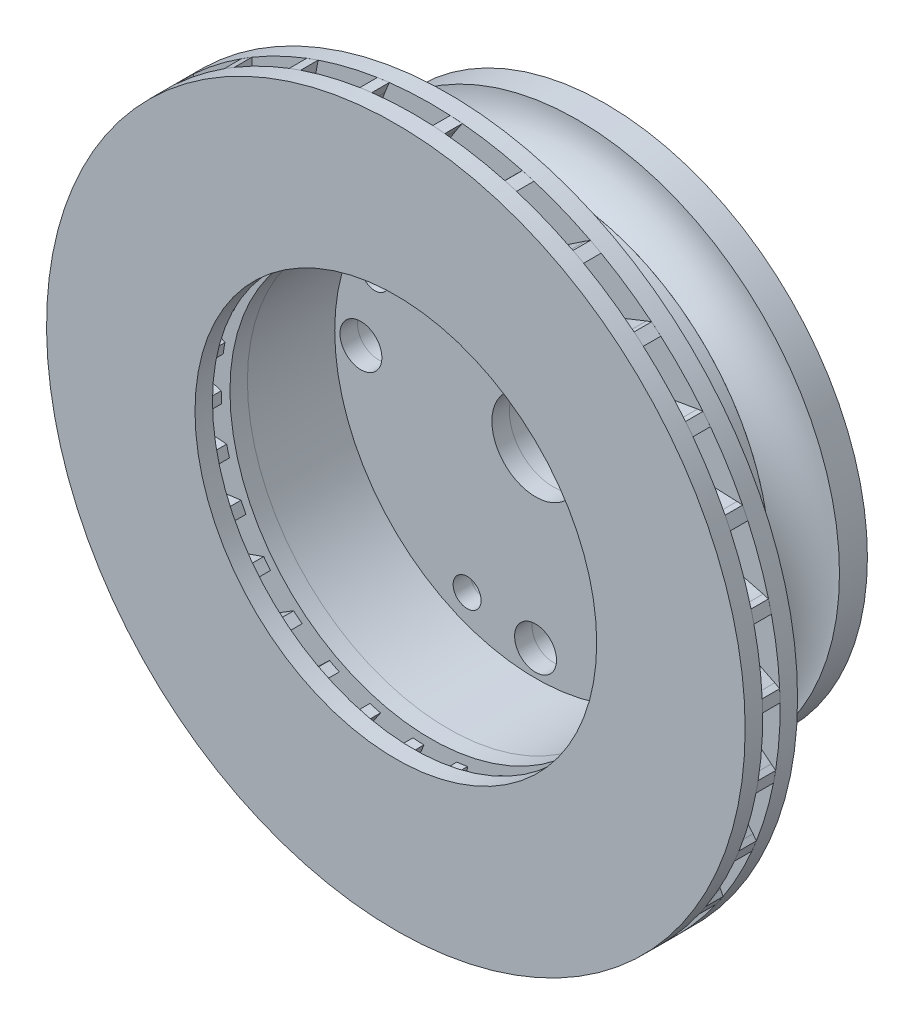
SolidWorks part; units mm, degrees
ref_plane "Front Plane" through (0, 0, 0) normal (0, 0, 1) x (1, 0, 0)
ref_plane "Top Plane" through (0, 0, 0) normal (0, 1, 0) x (1, 0, 0)
ref_plane "Right Plane" through (0, 0, 0) normal (1, 0, 0) x (0, 0, -1)
sketch "Sketch3" plane through (0, 0, 0) normal (1, 0, 0) x (0, 0, -1)
  line L0 (0, 0) -> (0, 75)
  line L1 (0, 75) -> (-8, 75)
  line L2 (-15, 62) -> (-15, 0)
  line L3 (-15, 0) -> (0, 0)
  line L4 (-15, 0) -> (-15.9175, 0)
  arc A0 (-8, 75) -> (-15, 62) centre (-23.5714, 75) cw
  point P10 (-5, 70)
  dimension "D1" = 8
  dimension "D2" = 75
  dimension "D3" = 13
  dimension "D4" = 15
  dimension "D5" = 0
revolve "Revolve1" add sketch "Sketch3" angle 360 about L4
sketch "Sketch4" plane through (0, 0, 15) normal (0, 0, 1) x (1, 0, 0)
  circle A2 centre (0, 0) radius 62
  circle A3 centre (0, 0) radius 62
  dimension "D1" = 0
extrude "Boss-Extrude2" add sketch "Sketch4" along normal blind 30 separate body
sketch "Sketch5" plane through (0, 0, 45) normal (0, 0, 1) x (1, 0, 0)
  circle A0 centre (0, 0) radius 100
  dimension "D1" = 200
extrude "Boss-Extrude3" add sketch "Sketch5" along normal blind 5 separate body
sketch "Sketch6" plane through (0, 0, 50) normal (0, 0, 1) x (1, 0, 0)
  line L0 (0, 0) -> (0, 8.2778)
  line L1 (44.3489, 88.0949) -> (45.7099, 88.9416)
  line L2 (45.9335, 85.5476) -> (47.2945, 86.3942)
  line L3 (47.2945, 86.3942) -> (48.7607, 87.3063)
  line L4 (48.7607, 87.3063) -> (45.7099, 88.9416)
  circle A1 centre (0, 0) radius 100 construction
  arc A2 (14.3838, 58.2504) -> (44.3489, 88.0949) centre (94, 8.2778) cw
  arc A4 (17.4091, 57.4188) -> (45.9335, 85.5476) centre (94, 8.2778) cw
  circle A5 centre (0, 0) radius 100
  circle A6 centre (0, 0) radius 100
  arc A7 (17.4091, 57.4188) -> (14.3838, 58.2504) centre (0, 0) ccw
  arc A8 (0, 8.2778) -> (44.3489, 88.0949) centre (94, 8.2778) cw construction
  arc A9 (3, 8.2778) -> (45.9335, 85.5476) centre (94, 8.2778) cw construction
  dimension "D1" = 94
  dimension "D4" = 120
  dimension "D2" = 0
  dimension "D3" = 3
extrude "Boss-Extrude4" add sketch "Sketch6" along normal blind 2.5 separate body contours A7 A4 L2 L3 L4 L1 A2
pattern_circular "CirPattern1" count 30 over 360 about axis through (0, 0, 0) along (0, 0, 1) of "Boss-Extrude4"
mirror "Mirror1" about plane through (0, 0, 52.5) normal (0, 0, 1) of bodies 106 105
sketch "Sketch7" plane through (0, 0, 0) normal (0, 0, -1) x (-1, 0, 0)
  circle A0 centre (0, 0) radius 57.5
  dimension "D1" = 115
extrude "Cut-Extrude1" cut sketch "Sketch7" against normal blind 134.5
combine bodies "Combine1" operation type add bodies to combine 112 108
combine bodies "Combine2" bodies to combine 105 113 111
sketch "Sketch8" plane through (0, 0, 15) normal (0, 0, -1) x (-1, 0, 0)
  circle A0 centre (0, 0) radius 62
  circle A1 centre (0, 0) radius 50
  circle A2 centre (0, 50) radius 6
  circle A3 centre (-19.5959, 46) radius 4
  circle A4 centre (46, 19.5959) radius 4
  circle A5 centre (50, 0) radius 6
  circle A6 centre (19.5959, -46) radius 4
  circle A7 centre (0, -50) radius 6
  circle A8 centre (-46, -19.5959) radius 4
  circle A9 centre (-50, 0) radius 6
  point P23 (0, 0)
  circle M3 centre (0, 0) radius 57.5
  circle M4 centre (0, 0) radius 62
  dimension "D1" = 100
  dimension "D2" = 12
  dimension "D3" = 8
  dimension "D4" = 20
  dimension "D5" = 4
extrude "Boss-Extrude5" add sketch "Sketch8" against normal blind 5 contours A9 A1 A3 A2 A4 A5 A6 A7 A8 M3 | M4 M3 | A9 A1 A8 A7 A6 A5 A4 A2 A3
sketch "Sketch9" plane through (0, 0, 15) normal (0, 0, -1) x (-1, 0, 0)
  circle A2 centre (0, 0) radius 62
  circle A3 centre (0, 0) radius 62
  circle M2 centre (0, 0) radius 62
  circle M3 centre (-46, -19.5959) radius 4
  circle M4 centre (0, -50) radius 6
  circle M5 centre (19.5959, -46) radius 4
  circle M6 centre (50, 0) radius 6
  circle M7 centre (46, 19.5959) radius 4
  circle M8 centre (0, 50) radius 6
  circle M9 centre (-19.5959, 46) radius 4
  circle M10 centre (-50, 0) radius 6
  dimension "D1" = 0
extrude "Boss-Extrude6" add sketch "Sketch9" along normal blind 15 contours M2 M3 M5 M7 M9 M10 M8 M6 M4
sketch "Sketch10" plane through (0, 0, 0) normal (0, 0, -1) x (-1, 0, 0)
  circle A0 centre (0, 0) radius 25
  dimension "D1" = 50
extrude "Boss-Extrude7" add sketch "Sketch10" along normal blind 13
sketch "Sketch11" plane through (0, 0, -13) normal (0, 0, -1) x (-1, 0, 0)
  circle A2 centre (0, 0) radius 23
  circle A3 centre (0, 0) radius 23
  dimension "D1" = 2
extrude "Cut-Extrude2" cut sketch "Sketch11" against normal blind 13
sketch "Sketch12" plane through (0, 0, 0) normal (0, 0, -1) x (-1, 0, 0)
  circle A0 centre (0, 0) radius 12.5
  dimension "D1" = 25
extrude "Cut-Extrude3" cut sketch "Sketch12" against normal blind 59
